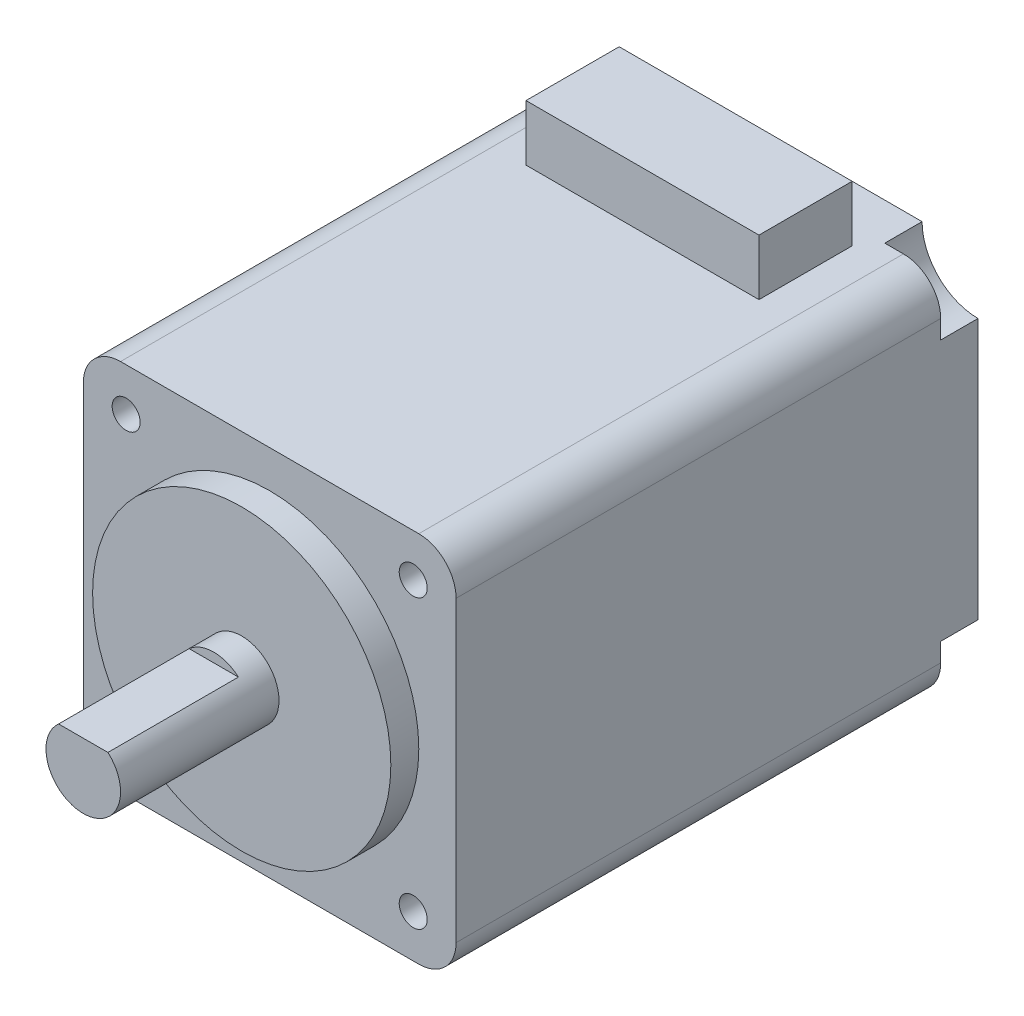
SolidWorks part; units mm, degrees
ref_plane "Plano frontal" through (0, 0, 0) normal (0, 0, 1) x (1, 0, 0)
ref_plane "Plano superior" through (0, 0, 0) normal (0, 1, 0) x (1, 0, 0)
ref_plane "Plano direito" through (0, 0, 0) normal (1, 0, 0) x (0, 0, -1)
sketch "Esboço1" plane through (0, 0, 0) normal (0, 0, 1) x (1, 0, 0)
  line L1 (-10, 10) -> (10, 10)
  line L2 (-10, 10) -> (-10, -10)
  line L3 (-10, -10) -> (10, -10)
  line L4 (10, 10) -> (10, -10)
  line L5 (-10, 10) -> (10, -10) construction
  line L6 (-10, -10) -> (10, 10) construction
  point P0 (0, 0)
  dimension "D1" = 20
extrude "Ressalto-extrusão1" add sketch "Esboço1" along normal blind 28
sketch "Esboço2" plane through (0, 0, 0) normal (0, 0, -1) x (-1, 0, 0)
  circle A0 centre (0, 0) radius 3.25
  circle A1 centre (-10, 10) radius 3
  circle A2 centre (10, 10) radius 3
  circle A3 centre (10, -10) radius 3
  circle A4 centre (-10, -10) radius 3
  dimension "D1" = 6.5
  dimension "D2" = 6
extrude "Corte-extrusão1" cut sketch "Esboço2" against normal blind 2 contours A1 | A0 | A2 | A3 | A4
sketch "Esboço3" plane through (0, 10, 0) normal (0, 1, 0) x (1, 0, 0)
  line L0 (7, 0) -> (-7, 0) construction
  line L1 (6.25, -8) -> (-6.25, -8)
  line L2 (6.25, -8) -> (6.25, -3)
  line L3 (6.25, -3) -> (-6.25, -3)
  line L4 (-6.25, -8) -> (-6.25, -3)
  point P6 (0, -3)
  dimension "D1" = 12.5
  dimension "D2" = 5
  dimension "D3" = 3
extrude "Ressalto-extrusão2" add sketch "Esboço3" along normal blind 3
fillet "Filete1" radius 2 4 edges at (10, -10, 15) (-10, -10, 15) (-10, 10, 15) (10, 10, 15)
sketch "Esboço4" plane through (0, 0, 28) normal (0, 0, 1) x (1, 0, 0)
  circle A0 centre (0, 0) radius 8
  dimension "D1" = 16
extrude "Ressalto-extrusão3" add sketch "Esboço4" along normal blind 1.5
sketch "Esboço5" plane through (0, 0, 29.5) normal (0, 0, 1) x (1, 0, 0)
  circle A0 centre (0, 0) radius 2
  dimension "D1" = 4
extrude "Ressalto-extrusão4" add sketch "Esboço5" along normal blind 8.5
sketch "Esboço6" plane through (0, 0, 38) normal (0, 0, 1) x (1, 0, 0)
  line L0 (0, 1.5) -> (0, -2) construction
  line L1 (-2.7106, 3.9094) -> (2.7106, 3.9094)
  line L2 (-2.7106, 3.9094) -> (-2.7106, 1.5)
  line L3 (-2.7106, 1.5) -> (2.7106, 1.5)
  line L4 (2.7106, 3.9094) -> (2.7106, 1.5)
  circle A0 centre (0, 0) radius 2 construction
  dimension "D1" = 3.5
extrude "Corte-extrusão2" cut sketch "Esboço6" against normal blind 7
sketch "Esboço7" plane through (0, 0, 28) normal (0, 0, 1) x (1, 0, 0)
  line L1 (7.7, -7.7) -> (-7.7, -7.7) construction
  line L2 (7.7, -7.7) -> (7.7, 7.7) construction
  line L3 (7.7, 7.7) -> (-7.7, 7.7) construction
  line L4 (-7.7, -7.7) -> (-7.7, 7.7) construction
  line L5 (7.7, -7.7) -> (-7.7, 7.7) construction
  line L6 (7.7, 7.7) -> (-7.7, -7.7) construction
  circle A0 centre (-7.7, 7.7) radius 0.75
  circle A1 centre (7.7, 7.7) radius 0.75
  circle A2 centre (7.7, -7.7) radius 0.75
  circle A3 centre (-7.7, -7.7) radius 0.75
  point P0 (0, 0)
  dimension "D2" = 1.5
  dimension "D1" = 15.4
extrude "Corte-extrusão3" cut sketch "Esboço7" against normal blind 5
